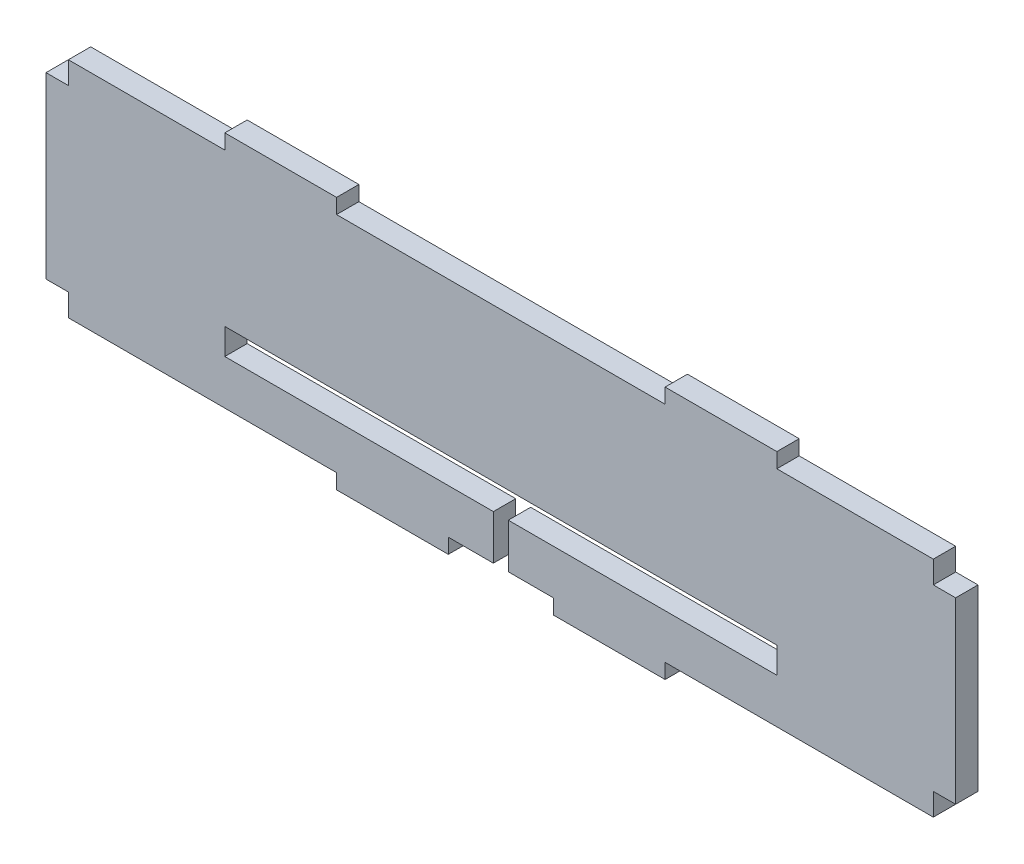
SolidWorks part; units mm, degrees
ref_plane "Front Plane" through (0, 0, 0) normal (0, 0, 1) x (1, 0, 0)
ref_plane "Top Plane" through (0, 0, 0) normal (0, 1, 0) x (1, 0, 0)
ref_plane "Right Plane" through (0, 0, 0) normal (1, 0, 0) x (0, 0, -1)
sketch "Sketch1" plane through (0, 0, 0) normal (0, 0, 1) x (1, 0, 0)
  line L0 (0, 0) -> (0, 43717.3993) construction
  line L1 (-5.9695, 0) -> (43711.4297, 0) construction
  line L2 (3, 0) -> (42, 0)
  line L4 (3, 0) -> (3, 30)
  line L6 (125.1, 0) -> (125.1, 30)
  line L7 (42, 0) -> (42, -2)
  line L8 (42, -2) -> (57, -2)
  line L9 (57, -2) -> (57, 0)
  line L10 (57, 0) -> (71.1, 0)
  line L11 (71.1, 0) -> (71.1, -2)
  line L12 (71.1, -2) -> (86.1, -2)
  line L13 (86.1, -2) -> (86.1, 0)
  line L14 (86.1, 0) -> (125.1, 0)
  line L15 (64.05, 0) -> (64.05, -50000) construction
  line L16 (27, 9.5) -> (101.1, 9.5)
  line L17 (27, 9.5) -> (27, 6)
  line L19 (101.1, 9.5) -> (101.1, 6)
  line L20 (65.05, 0) -> (65.05, 6)
  line L21 (63.05, 0) -> (65.05, 0)
  line L22 (63.05, 0) -> (63.05, 6)
  line L25 (27, 6) -> (63.05, 6)
  line L26 (65.05, 6) -> (101.1, 6)
  line L27 (3, 30) -> (27, 30)
  line L29 (42, 30) -> (42, 32)
  line L30 (42, 32) -> (27, 32)
  line L31 (27, 30) -> (27, 32)
  line L32 (42, 30) -> (86.1, 30)
  line L33 (125.1, 30) -> (101.1, 30)
  line L34 (101.1, 30) -> (101.1, 32)
  line L35 (86.1, 32) -> (101.1, 32)
  line L36 (86.1, 30) -> (86.1, 32)
  line L37 (125.1, 3) -> (122.1, 3)
  line L38 (3, 0) -> (6, 0)
  line L39 (3, 0) -> (3, 3)
  line L40 (3, 3) -> (6, 3)
  line L41 (6, 0) -> (6, 3)
  line L42 (122.1, 0) -> (122.1, 3)
  line L43 (125.1, 0) -> (122.1, 0)
  line L44 (125.1, 0) -> (125.1, 3)
  line L45 (-14.82, 15) -> (49985.18, 15) construction
  line L46 (125.1, 30) -> (122.1, 30)
  line L47 (122.1, 30) -> (122.1, 27)
  line L48 (125.1, 27) -> (122.1, 27)
  line L49 (125.1, 30) -> (125.1, 27)
  line L50 (3, 27) -> (6, 27)
  line L51 (6, 30) -> (6, 27)
  line L52 (3, 30) -> (6, 30)
  line L53 (3, 30) -> (3, 27)
  point P36 (64.05, 30)
  dimension "D1" = 122.1
  dimension "D2" = 30
  dimension "D3" = 15
  dimension "D4" = 15
  dimension "D5" = 14.1
  dimension "D6" = 15
  dimension "D7" = 2
  dimension "D8" = 2
  dimension "D9" = 15
  dimension "D11" = 6
  dimension "D12" = 3.5
  dimension "D13" = 15
  dimension "D14" = 2
extrude "Boss-Extrude3" add sketch "Sketch1" along normal blind 3 contours L36 L32 L29 L30 L31 L27 L4 L2 L7 L8 L9 L10 L22 L25 L17 L16 L19 L26 L20 L11 L12 L13 L14 L6 L33 L34 L35
